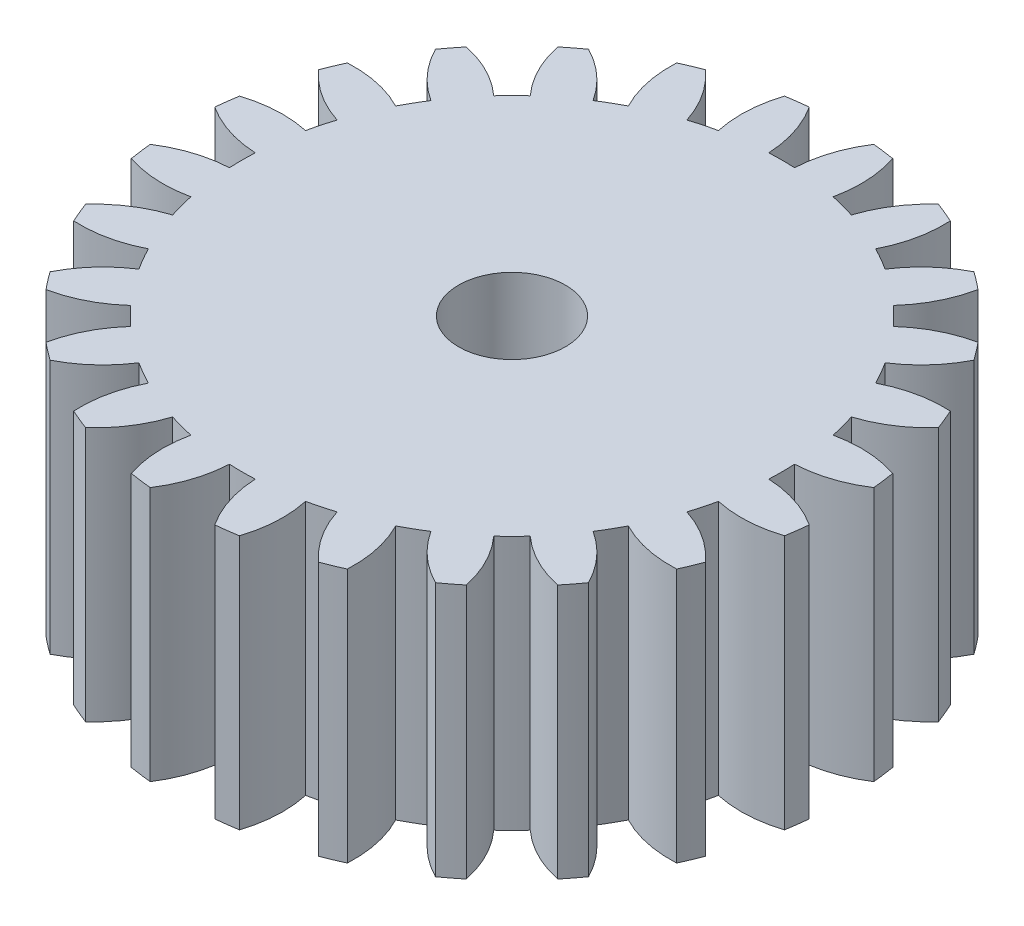
SolidWorks part; units mm, degrees
material "eSUN Tough Resin"
ref_plane "Front Plane" through (0, 0, 0) normal (0, 0, 1) x (1, 0, 0)
ref_plane "Top Plane" through (0, 0, 0) normal (0, 1, 0) x (1, 0, 0)
ref_plane "Right Plane" through (0, 0, 0) normal (1, 0, 0) x (0, 0, -1)
sketch "Sketch1" plane through (0, 0, 0) normal (0, 1, 0) x (1, 0, 0)
  circle A0 centre (0, 0) radius 6
  circle A1 centre (0, 0) radius 6.5
  circle A2 centre (0, 0) radius 5.3
  dimension "D1" = 12
  dimension "D2" = 13
  dimension "D3" = 1.2
extrude "Boss-Extrude1" add sketch "Sketch1" along normal mid plane 5 contours A1 A0 | A0 A2 | A2
sketch "Sketch3" plane through (0, 0, 0) normal (0, 1, 0) x (1, 0, 0)
  line L0 (0, 0) -> (0, 6.5) construction
  line L1 (-0.3924, 5.9872) -> (0.3924, 5.9872) construction
  line L2 (-0.253, 5.294) -> (0, 0) construction
  line L3 (0, 4.909) -> (-1.017, 7.7032) construction
  line L4 (0, 0) -> (0.8484, 6.4444) construction
  line L5 (0.3924, 5.9872) -> (1.1705, 5.8847) construction
  circle A0 centre (0, 0) radius 6.5 construction
  arc A1 (-2.0974, 7.4816) -> (-0.253, 5.294) centre (-2.606, 5.1815) cw
  arc A2 (2.0974, 7.4816) -> (0.253, 5.294) centre (2.606, 5.1815) ccw
  circle A3 centre (0, 0) radius 5.3 construction
  arc A4 (0.253, 5.294) -> (-0.253, 5.294) centre (0, 0) ccw
  circle A5 centre (0, 0) radius 6 construction
  circle A6 centre (0, 0) radius 6.5 construction
  circle A7 centre (0, 0) radius 7.77
  arc A8 (2.0974, 7.4816) -> (-2.0974, 7.4816) centre (0, 0) ccw
  dimension "D2" = 20
  dimension "D3" = 7.5
  dimension "D1" = 1.27
extrude "Cut-Extrude1" cut sketch "Sketch3" against normal through all both and the other way through all
fillet "Fillet2" [suppressed] radius 0.15
pattern_circular "CirPattern1" count 24 over 360 about axis through (0, 0, 0) along (0, 1, 0) of "Cut-Extrude1", "Fillet2"
sketch "Sketch4" plane through (0, 0, 0) normal (0, 1, 0) x (1, 0, 0)
  circle A0 centre (0, 0) radius 1.05
  dimension "D1" = 2.1
extrude "Cut-Extrude2" cut sketch "Sketch4" along normal through all both and the other way through all
equation "\"Module\"= .5"
equation "\"Number of Teeth\"= 24"
equation "\"D1@Sketch1\"=\"Module\"* \"Number of Teeth\""
equation "\"D2@Sketch1\"=(\"Number of Teeth\" + 2) * \"Module\""
equation "\"D3@Sketch1\"=\"Module\" * if( \"Module\" => 1.25, 2.25, 2.4)"
equation "\"D3@Sketch3\"=180 / \"Number of Teeth\""
equation "\"D1@Fillet2\"=.3 * \"Module\""
equation "\"D1@CirPattern1\"=\"Number of Teeth\""
